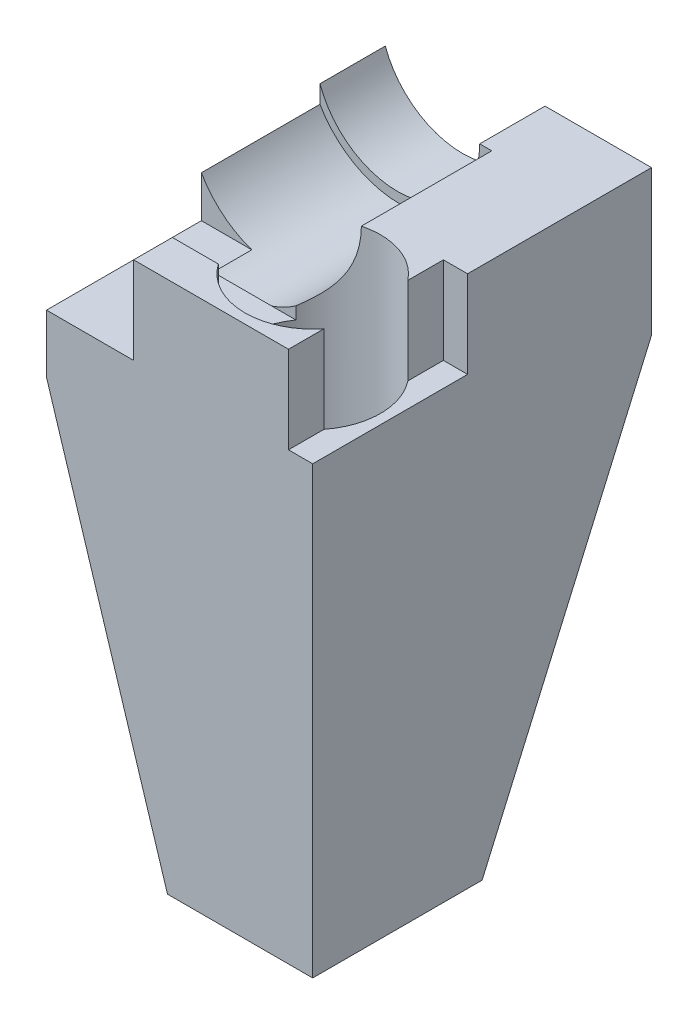
SolidWorks part; units mm, degrees
ref_plane "Front Plane" through (0, 0, 0) normal (0, 0, 1) x (1, 0, 0)
ref_plane "Top Plane" through (0, 0, 0) normal (0, 1, 0) x (1, 0, 0)
ref_plane "Right Plane" through (0, 0, 0) normal (1, 0, 0) x (0, 0, -1)
sketch "Sketch1" plane through (0, 0, 0) normal (0, 1, 0) x (1, 0, 0)
  line L1 (0, 0) -> (55, 0)
  line L2 (0, 0) -> (0, 70)
  line L3 (0, 70) -> (55, 70)
  line L4 (55, 0) -> (55, 70)
  dimension "D1" = 55
  dimension "D2" = 70
extrude "Boss-Extrude1" add sketch "Sketch1" along normal blind 110
sketch "Sketch2" plane through (0, 110, 0) normal (0, 1, 0) x (1, 0, 0)
  line L0 (55, 0) -> (55, 70) construction
  line L1 (0, 0) -> (55, 0) construction
  circle A0 centre (39, 16) radius 14
  point P2 (0, 0)
  point P3 (38.4456, 15.515)
  dimension "D1" = 28
  dimension "D2" = 16
  dimension "D3" = 16
extrude "Cut-Extrude1" cut sketch "Sketch2" against normal blind 108
sketch "Sketch3" plane through (0, 110, 0) normal (0, 1, 0) x (1, 0, 0)
  line L0 (0, 0) -> (55, 0) construction
  line L1 (55, 0) -> (50, 0)
  line L2 (55, 0) -> (55, 32)
  line L3 (55, 32) -> (50, 32)
  line L4 (50, 0) -> (50, 32)
  line L5 (0, 0) -> (18, 0)
  line L6 (0, 0) -> (0, 32)
  line L7 (0, 32) -> (18, 32)
  line L8 (18, 0) -> (18, 8)
  line L9 (18, 8) -> (31.3328, 8)
  line L11 (18, 24) -> (31.3328, 24)
  line L12 (31.3328, 8) -> (31.3328, 24)
  line L13 (18, 24) -> (18, 32)
  dimension "D1" = 32
  dimension "D2" = 5
  dimension "D3" = 32
  dimension "D4" = 18
  dimension "D5" = 16
  dimension "D6" = 8
extrude "Cut-Extrude2" cut sketch "Sketch3" against normal blind 18
sketch "Sketch4" plane through (0, 0, -70) normal (0, 0, -1) x (-1, 0, 0)
  line L0 (-55, 110) -> (0, 110) construction
  line L2 (0, 110) -> (0, 0) construction
  circle A0 centre (-16, 110) radius 17
  point P2 (0, 0)
  dimension "D1" = 34
  dimension "D3" = 16
  dimension "D2" = 0
extrude "Cut-Extrude3" cut sketch "Sketch4" against normal blind 13.5 contours A0
sketch "Sketch5" plane through (0, 0, -56.5) normal (0, 0, -1) x (-1, 0, 0)
  line L0 (0, 110) -> (-33, 110) construction
  circle A0 centre (-16.5, 110) radius 19
  dimension "D1" = 38
extrude "Cut-Extrude5" cut sketch "Sketch5" against normal up to surface (32.5 mm away) up to face at (22.7554, 101, -24)
sketch "Sketch8" plane through (55, 0, 0) normal (1, 0, 0) x (0, 0, -1)
  line L0 (70, 0) -> (70, 80)
  line L1 (70, 110) -> (70, 0) construction
  line L2 (70, 80) -> (35, 0)
  line L3 (0, 0) -> (70, 0) construction
  line L4 (35, 0) -> (70, 0)
  dimension "D1" = 35
  dimension "D2" = 80
extrude "Cut-Extrude7" cut sketch "Sketch8" against normal up to next
sketch "Sketch9" plane through (0, 0, 0) normal (0, 0, 1) x (1, 0, 0)
  line L0 (0, 0) -> (25, 0)
  line L1 (0, 0) -> (55, 0) construction
  line L2 (25, 0) -> (0, 80)
  line L3 (0, 92) -> (0, 0) construction
  line L4 (0, 80) -> (0, 0)
  dimension "D1" = 80
  dimension "D2" = 25
extrude "Cut-Extrude8" cut sketch "Sketch9" against normal up to next
